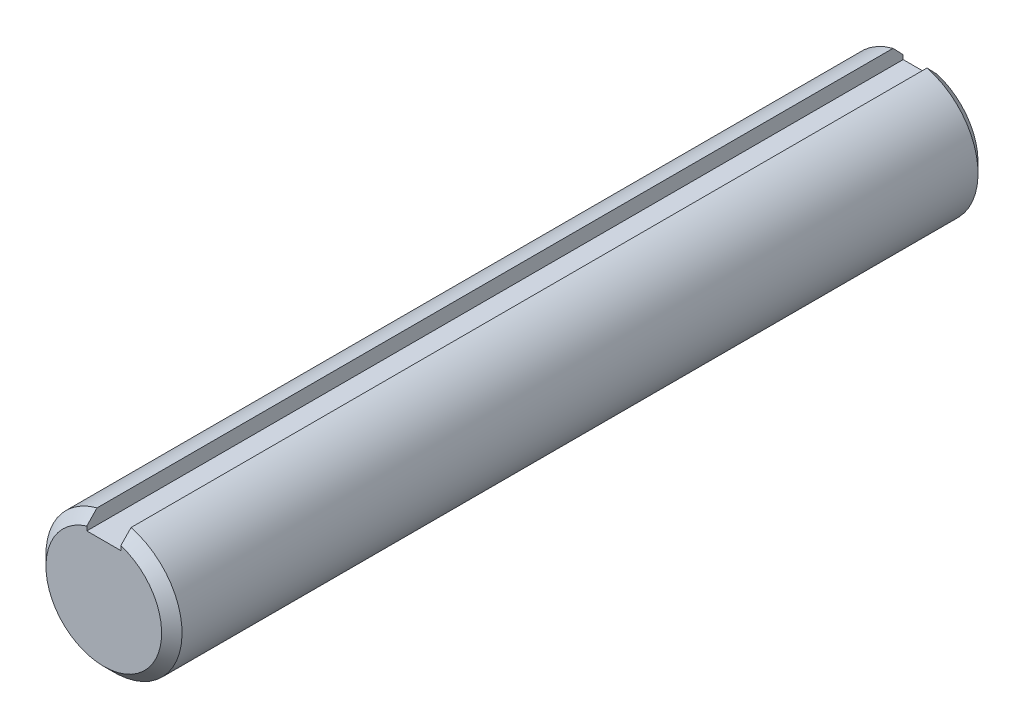
SolidWorks part; units mm, degrees
ref_plane "Front" through (0, 0, 0) normal (0, 0, 1) x (1, 0, 0)
ref_plane "Top" through (0, 0, 0) normal (0, 1, 0) x (1, 0, 0)
ref_plane "Right" through (0, 0, 0) normal (1, 0, 0) x (0, 0, -1)
sketch "Sketch1" plane through (0, 0, 0) normal (0, 0, 1) x (1, 0, 0)
  circle A0 centre (0, 0) radius 12.7
  dimension "dia" = 25.4
extrude "Extrude1" add sketch "Sketch1" along normal mid plane 152.4
sketch "Sketch2" plane through (0, 0, 0) normal (1, 0, 0) x (0, 0, -1)
  point P0 (-76.2, 12.7)
  point P1 (76.2, 12.7)
  point P2 (76.2, -12.7)
chamfer "Chamfer1" distance 1.905 angle 45 2 edges at (12.7, 0, -76.2) (12.7, 0, 76.2)
sketch "Sketch3" plane through (0, 0, 0) normal (0, 0, 1) x (1, 0, 0)
  line L1 (-3.175, 12.7) -> (3.175, 12.7)
  line L2 (-3.175, 12.7) -> (-3.175, 9.525)
  line L3 (-3.175, 9.525) -> (3.175, 9.525)
  line L4 (3.175, 12.7) -> (3.175, 9.525)
  dimension "key wd" = 6.35
  dimension "key dp" = 3.175
extrude "Extrude2" cut sketch "Sketch3" against normal through all and the other way through all
equation "\"D1@Chamfer1\" = \"dia@Sketch1\" * .075"
